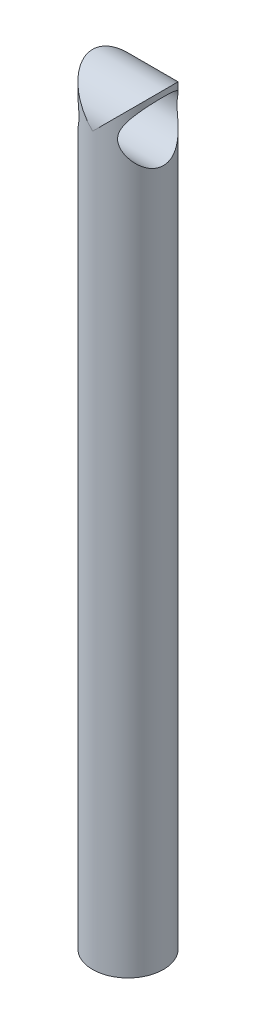
SolidWorks part; units mm, degrees
ref_plane "Front Plane" through (0, 0, 0) normal (0, 0, 1) x (1, 0, 0)
ref_plane "Top Plane" through (0, 0, 0) normal (0, 1, 0) x (1, 0, 0)
ref_plane "Right Plane" through (0, 0, 0) normal (1, 0, 0) x (0, 0, -1)
sketch "Sketch2" plane through (0, 0, 0) normal (0, 1, 0) x (1, 0, 0)
  circle A0 centre (0, 0) radius 4.7308
  dimension "D1" = 9.4615
extrude "Boss-Extrude2" add sketch "Sketch2" along normal blind 101.6
sketch "Sketch3" plane through (0, 0, 0) normal (1, 0, 0) x (0, 0, -1)
  line L0 (4.7308, 0) -> (4.7308, 101.6) construction
  line L2 (4.7308, 101.6) -> (-4.7308, 101.6) construction
  line L3 (-4.7308, 101.6) -> (-4.7308, 0) construction
  line L6 (-4.7308, 92.1385) -> (4.7308, 92.1385)
  line L7 (-4.7308, 92.1385) -> (-4.7308, 101.6)
  line L8 (-4.7308, 101.6) -> (4.7308, 101.6)
  line L9 (4.7308, 92.1385) -> (4.7308, 101.6)
  line L10 (-4.7308, 92.1385) -> (4.7308, 101.6) construction
  line L11 (-4.7308, 101.6) -> (4.7308, 92.1385) construction
  circle A0 centre (0, 96.8692) radius 4.7308
  circle A1 centre (0, 96.8692) radius 3.9688
  dimension "D1" = 7.9375
extrude "Cut-Extrude1" cut sketch "Sketch3" against normal through all both and the other way through all contours A1 | A0 L8 L7 | A0 L9 L8
